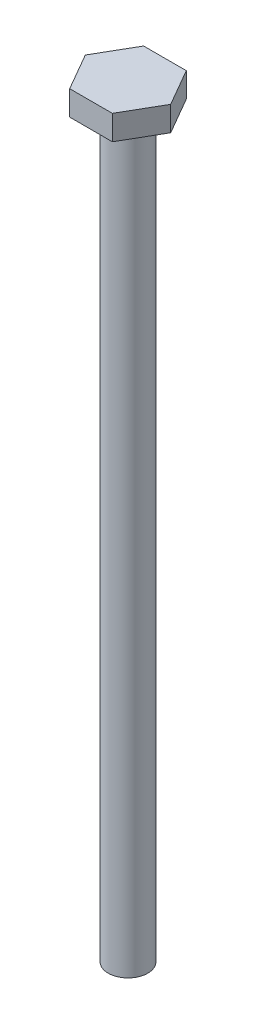
SolidWorks part; units mm, degrees
material "Alloy Steel"
ref_plane "Front Plane" through (0, 0, 0) normal (0, 0, 1) x (1, 0, 0)
ref_plane "Top Plane" through (0, 0, 0) normal (0, 1, 0) x (1, 0, 0)
ref_plane "Right Plane" through (0, 0, 0) normal (1, 0, 0) x (0, 0, -1)
sketch "Sketch1" plane through (0, 0, 0) normal (0, 1, 0) x (1, 0, 0)
  line L1 (4.3301, 0) -> (2.1651, 3.75)
  line L2 (2.1651, 3.75) -> (-2.1651, 3.75)
  line L3 (-2.1651, 3.75) -> (-4.3301, 0)
  line L4 (-4.3301, 0) -> (-2.1651, -3.75)
  line L5 (-2.1651, -3.75) -> (2.1651, -3.75)
  line L6 (2.1651, -3.75) -> (4.3301, 0)
  circle A0 centre (0, 0) radius 3.75 construction
  dimension "D1" = 7.5
extrude "Boss-Extrude1" add sketch "Sketch1" along normal blind 2.5
sketch "Sketch2" plane through (0, 0, 0) normal (0, -1, 0) x (1, 0, 0)
  circle A0 centre (0, 0) radius 2
  dimension "D1" = 4
extrude "Boss-Extrude2" add sketch "Sketch2" along normal blind 75
